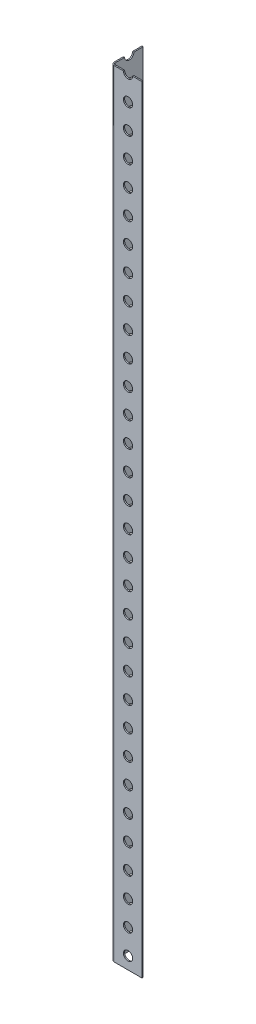
SolidWorks part; units mm, degrees
material "AISI 1020"
ref_plane "Front Plane" through (0, 0, 0) normal (0, 0, 1) x (1, 0, 0)
ref_plane "Top Plane" through (0, 0, 0) normal (0, 1, 0) x (1, 0, 0)
ref_plane "Right Plane" through (0, 0, 0) normal (1, 0, 0) x (0, 0, -1)
sketch "Sketch1" plane through (0, 0, 0) normal (0, 1, 0) x (1, 0, 0)
  line L0 (1.27, 30.48) -> (30.48, 30.48)
  line L1 (0, 0) -> (31.75, 0)
  line L2 (0, 0) -> (0, 31.75)
  line L3 (0, 31.75) -> (31.75, 31.75)
  line L4 (31.75, 0) -> (31.75, 31.75)
  line L5 (30.48, 1.27) -> (30.48, 30.48)
  line L6 (1.27, 1.27) -> (30.48, 1.27)
  line L7 (1.27, 1.27) -> (1.27, 30.48)
  line L8 (1.27, 30.48) -> (1.27, 31.75)
  line L9 (30.48, 1.27) -> (31.75, 1.27)
  dimension "D1" = 31.75
  dimension "D2" = 31.75
  dimension "D3" = 1.27
extrude "Boss-Extrude1" add sketch "Sketch1" along normal blind 1219.2 contours L9 L6 L7 L8 L3 L2 L1 L4
sketch "Sketch3" plane through (0, 0, 0) normal (-1, 0, 0) x (0, 0, 1)
  line L0 (-17.4625, 0) -> (-17.4625, 12.7) construction
  line L2 (-31.75, 1219.2) -> (-31.75, 0) construction
  circle A0 centre (-17.4625, 12.7) radius 4.7625
  circle A1 centre (-17.4625, 38.1) radius 4.7625
  circle A2 centre (-17.4625, 63.5) radius 4.7625
  circle A3 centre (-17.4625, 88.9) radius 4.7625
  circle A4 centre (-17.4625, 114.3) radius 4.7625
  circle A5 centre (-17.4625, 139.7) radius 4.7625
  circle A6 centre (-17.4625, 165.1) radius 4.7625
  circle A7 centre (-17.4625, 190.5) radius 4.7625
  circle A8 centre (-17.4625, 215.9) radius 4.7625
  circle A9 centre (-17.4625, 241.3) radius 4.7625
  circle A10 centre (-17.4625, 266.7) radius 4.7625
  circle A11 centre (-17.4625, 292.1) radius 4.7625
  circle A12 centre (-17.4625, 317.5) radius 4.7625
  circle A13 centre (-17.4625, 342.9) radius 4.7625
  circle A14 centre (-17.4625, 368.3) radius 4.7625
  circle A15 centre (-17.4625, 393.7) radius 4.7625
  circle A16 centre (-17.4625, 419.1) radius 4.7625
  circle A17 centre (-17.4625, 444.5) radius 4.7625
  circle A18 centre (-17.4625, 469.9) radius 4.7625
  circle A19 centre (-17.4625, 495.3) radius 4.7625
  circle A20 centre (-17.4625, 520.7) radius 4.7625
  circle A21 centre (-17.4625, 546.1) radius 4.7625
  circle A22 centre (-17.4625, 571.5) radius 4.7625
  circle A23 centre (-17.4625, 596.9) radius 4.7625
  circle A24 centre (-17.4625, 622.3) radius 4.7625
  circle A25 centre (-17.4625, 647.7) radius 4.7625
  circle A26 centre (-17.4625, 673.1) radius 4.7625
  circle A27 centre (-17.4625, 698.5) radius 4.7625
  circle A28 centre (-17.4625, 723.9) radius 4.7625
  circle A29 centre (-17.4625, 749.3) radius 4.7625
  circle A30 centre (-17.4625, 774.7) radius 4.7625
  circle A31 centre (-17.4625, 800.1) radius 4.7625
  circle A32 centre (-17.4625, 825.5) radius 4.7625
  circle A33 centre (-17.4625, 850.9) radius 4.7625
  circle A34 centre (-17.4625, 876.3) radius 4.7625
  circle A35 centre (-17.4625, 901.7) radius 4.7625
  circle A36 centre (-17.4625, 927.1) radius 4.7625
  circle A37 centre (-17.4625, 952.5) radius 4.7625
  circle A38 centre (-17.4625, 977.9) radius 4.7625
  circle A39 centre (-17.4625, 1003.3) radius 4.7625
  circle A40 centre (-17.4625, 1028.7) radius 4.7625
  circle A41 centre (-17.4625, 1054.1) radius 4.7625
  circle A42 centre (-17.4625, 1079.5) radius 4.7625
  circle A43 centre (-17.4625, 1104.9) radius 4.7625
  circle A44 centre (-17.4625, 1130.3) radius 4.7625
  circle A45 centre (-17.4625, 1155.7) radius 4.7625
  circle A46 centre (-17.4625, 1181.1) radius 4.7625
  circle A47 centre (-17.4625, 1206.5) radius 4.7625
  dimension "D1" = 9.525
  dimension "D2" = 12.7
  dimension "D4" = 14.2875
  dimension "D3" = 48
extrude "Cut-Extrude1" cut sketch "Sketch3" against normal up to next (1.27 mm away)
sketch "Sketch4" plane through (0, 0, 0) normal (0, 0, 1) x (1, 0, 0)
  line L0 (17.4625, 1219.2) -> (17.4625, 1206.5) construction
  line L2 (31.75, 1219.2) -> (31.75, 0) construction
  circle A0 centre (17.4625, 1206.5) radius 4.7625
  circle A1 centre (17.4625, 1181.1) radius 4.7625
  circle A2 centre (17.4625, 1155.7) radius 4.7625
  circle A3 centre (17.4625, 1130.3) radius 4.7625
  circle A4 centre (17.4625, 1104.9) radius 4.7625
  circle A5 centre (17.4625, 1079.5) radius 4.7625
  circle A6 centre (17.4625, 1054.1) radius 4.7625
  circle A7 centre (17.4625, 1028.7) radius 4.7625
  circle A8 centre (17.4625, 1003.3) radius 4.7625
  circle A9 centre (17.4625, 977.9) radius 4.7625
  circle A10 centre (17.4625, 952.5) radius 4.7625
  circle A11 centre (17.4625, 927.1) radius 4.7625
  circle A12 centre (17.4625, 901.7) radius 4.7625
  circle A13 centre (17.4625, 876.3) radius 4.7625
  circle A14 centre (17.4625, 850.9) radius 4.7625
  circle A15 centre (17.4625, 825.5) radius 4.7625
  circle A16 centre (17.4625, 800.1) radius 4.7625
  circle A17 centre (17.4625, 774.7) radius 4.7625
  circle A18 centre (17.4625, 749.3) radius 4.7625
  circle A19 centre (17.4625, 723.9) radius 4.7625
  circle A20 centre (17.4625, 698.5) radius 4.7625
  circle A21 centre (17.4625, 673.1) radius 4.7625
  circle A22 centre (17.4625, 647.7) radius 4.7625
  circle A23 centre (17.4625, 622.3) radius 4.7625
  circle A24 centre (17.4625, 596.9) radius 4.7625
  circle A25 centre (17.4625, 571.5) radius 4.7625
  circle A26 centre (17.4625, 546.1) radius 4.7625
  circle A27 centre (17.4625, 520.7) radius 4.7625
  circle A28 centre (17.4625, 495.3) radius 4.7625
  circle A29 centre (17.4625, 469.9) radius 4.7625
  circle A30 centre (17.4625, 444.5) radius 4.7625
  circle A31 centre (17.4625, 419.1) radius 4.7625
  circle A32 centre (17.4625, 393.7) radius 4.7625
  circle A33 centre (17.4625, 368.3) radius 4.7625
  circle A34 centre (17.4625, 342.9) radius 4.7625
  circle A35 centre (17.4625, 317.5) radius 4.7625
  circle A36 centre (17.4625, 292.1) radius 4.7625
  circle A37 centre (17.4625, 266.7) radius 4.7625
  circle A38 centre (17.4625, 241.3) radius 4.7625
  circle A39 centre (17.4625, 215.9) radius 4.7625
  circle A40 centre (17.4625, 190.5) radius 4.7625
  circle A41 centre (17.4625, 165.1) radius 4.7625
  circle A42 centre (17.4625, 139.7) radius 4.7625
  circle A43 centre (17.4625, 114.3) radius 4.7625
  circle A44 centre (17.4625, 88.9) radius 4.7625
  circle A45 centre (17.4625, 63.5) radius 4.7625
  circle A46 centre (17.4625, 38.1) radius 4.7625
  circle A47 centre (17.4625, 12.7) radius 4.7625
  dimension "D1" = 9.525
  dimension "D2" = 12.7
  dimension "D4" = 14.2875
  dimension "D3" = 48
extrude "Cut-Extrude2" cut sketch "Sketch4" against normal up to next (1.27 mm away)
fillet "Fillet1" radius 3.175 1 edges at (0, 609.6, 0)
fillet "Fillet2" radius 1.5875 1 edges at (1.27, 609.6, -1.27)
sketch "Sketch5" plane through (0, 1219.2, 0) normal (0, 1, 0) x (1, 0, 0)
  line L12 (0, 31.75) -> (0, 3.175)
  line L13 (3.175, 0) -> (31.75, 0)
  line L14 (31.75, 0) -> (31.75, 1.27)
  line L15 (31.75, 1.27) -> (2.8575, 1.27)
  line L16 (1.27, 2.8575) -> (1.27, 31.75)
  line L17 (1.27, 31.75) -> (0, 31.75)
  line L18 (0, 31.75) -> (0, 3.175)
  line L19 (3.175, 0) -> (31.75, 0)
  line L20 (31.75, 0) -> (31.75, 1.27)
  line L21 (31.75, 1.27) -> (2.8575, 1.27)
  line L22 (1.27, 2.8575) -> (1.27, 31.75)
  line L23 (1.27, 31.75) -> (0, 31.75)
  arc A4 (0, 3.175) -> (3.175, 0) centre (3.175, 3.175) ccw
  arc A5 (1.27, 2.8575) -> (2.8575, 1.27) centre (2.8575, 2.8575) ccw
  arc A6 (0, 3.175) -> (3.175, 0) centre (3.175, 3.175) ccw
  arc A7 (1.27, 2.8575) -> (2.8575, 1.27) centre (2.8575, 2.8575) ccw
  dimension "D1" = 0
extrude "Cut-Extrude3" cut sketch "Sketch5" against normal blind 419.1
